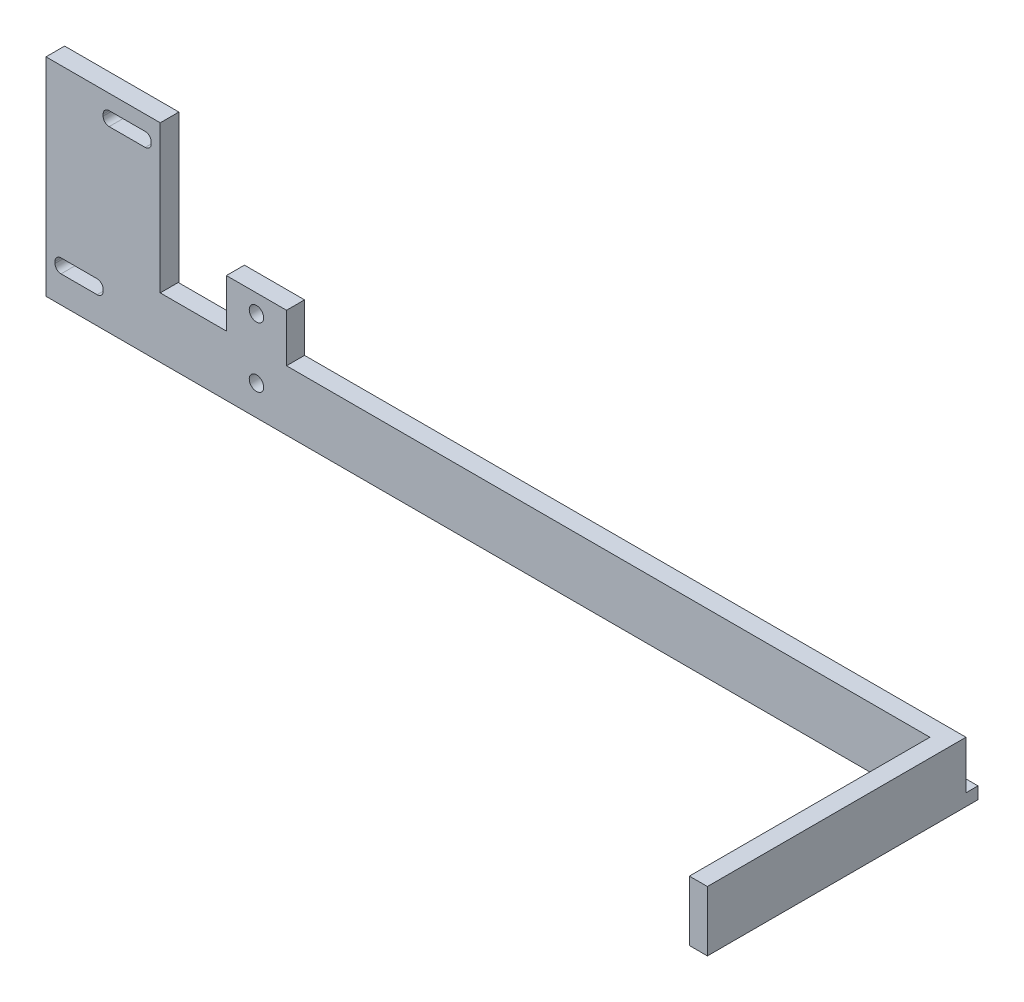
SolidWorks part; units mm, degrees
ref_plane "Спереди" through (0, 0, 0) normal (0, 0, 1) x (1, 0, 0)
ref_plane "Сверху" through (0, 0, 0) normal (0, 1, 0) x (1, 0, 0)
ref_plane "Справа" through (0, 0, 0) normal (1, 0, 0) x (0, 0, -1)
sketch "Эскиз1" plane through (0, 0, 0) normal (0, 1, 0) x (1, 0, 0)
  line L1 (-87, 21.5) -> (-87, 18.5)
  line L2 (-87, 18.5) -> (-60, 18.5)
  line L3 (63, -21.5) -> (60, -21.5)
  line L4 (63, 21.5) -> (63, -21.5)
  line L5 (60, -21.5) -> (60, 18.5)
  line L7 (-60, 18.5) -> (60, 18.5)
  line L12 (-87, 21.5) -> (63, 21.5)
  point P0 (0, 0)
  point P15 (0, 23.5)
extrude "Бобышка-Вытянуть1" add sketch "Эскиз1" along normal blind 10
sketch "Эскиз2" plane through (0, 0, -21.5) normal (0, 0, -1) x (-1, 0, 0)
  line L1 (47, 0) -> (57, 0)
  line L2 (47, 0) -> (47, 18)
  line L3 (47, 18) -> (57, 18)
  line L4 (57, 0) -> (57, 18)
  line L5 (47, 0) -> (57, 18) construction
  line L6 (47, 18) -> (57, 0) construction
  point P7 (52, 9)
extrude "Бобышка-Вытянуть2" add sketch "Эскиз2" against normal blind 3
sketch "Эскиз3" plane through (0, 0, -21.5) normal (0, 0, -1) x (-1, 0, 0)
  circle A1 centre (52, 15) radius 1.2
  circle A2 centre (52, 5) radius 1.2
extrude "Вырез-Вытянуть1" cut sketch "Эскиз3" against normal through all
sketch "Эскиз4" plane through (0, 0, -21.5) normal (0, 0, -1) x (-1, 0, 0)
  line L0 (87, 10) -> (87, 0) construction
  line L1 (-63, 0) -> (87, 0)
  line L2 (-63, 0) -> (-63, 2)
  line L3 (-63, 2) -> (87, 2)
  line L4 (87, 0) -> (87, 2)
  line L5 (-63, 0) -> (87, 2) construction
  line L6 (-63, 2) -> (87, 0) construction
  point P4 (12, 1)
  point P8 (0, 0)
  point P9 (0, 0)
  point P10 (0, 0)
  point P11 (0, 0)
  point P12 (0, 0)
  point P13 (87, 0)
  point P14 (87, 0)
  point P15 (0, 0)
  point P16 (87, 0)
  point P17 (0, 0)
  point P18 (0, 0)
extrude "Бобышка-Вытянуть3" add sketch "Эскиз4" along normal blind 2
sketch "Эскиз5" plane through (0, 0, -18.5) normal (0, 0, 1) x (1, 0, 0)
  line L0 (-87, 0) -> (-87, 34.5)
  line L1 (-87, 34.5) -> (-68, 34.5)
  line L2 (-68, 34.5) -> (-68, 0)
  line L3 (-87, 0) -> (60, 0) construction
  line L4 (-68, 0) -> (-87, 0)
extrude "Бобышка-Вытянуть4" add sketch "Эскиз5" against normal blind 3.1
sketch "Эскиз7" plane through (0, 0, -18.5) normal (0, 0, 1) x (1, 0, 0)
  line L0 (-77.5, 32) -> (-77.5, 29.7)
  line L6 (-69.5, 32) -> (-77.5, 32)
  line L7 (-69.5, 32) -> (-69.5, 29.7)
  line L8 (-69.5, 29.7) -> (-77.5, 29.7)
  line L11 (-85.5, 4.4898) -> (-77.5, 4.4898)
  line L12 (-85.5, 4.4898) -> (-85.5, 6.7898)
  line L13 (-85.5, 6.7898) -> (-77.5, 6.7898)
  line L14 (-77.5, 4.4898) -> (-77.5, 6.7898)
  point P7 (0, 0)
extrude "Вырез-Вытянуть2" cut sketch "Эскиз7" against normal blind 10
fillet "Скругление1" radius 1 8 edges at (-69.5, 32, -20.05) (-69.5, 29.7, -20.05) (-77.5, 32, -20.05) (-77.5, 29.7, -20.05) (-85.5, 4.4898, -20.05) (-77.5, 4.4898, -20.05) (-77.5, 6.7898, -20.05) (-85.5, 6.7898, -20.05)
